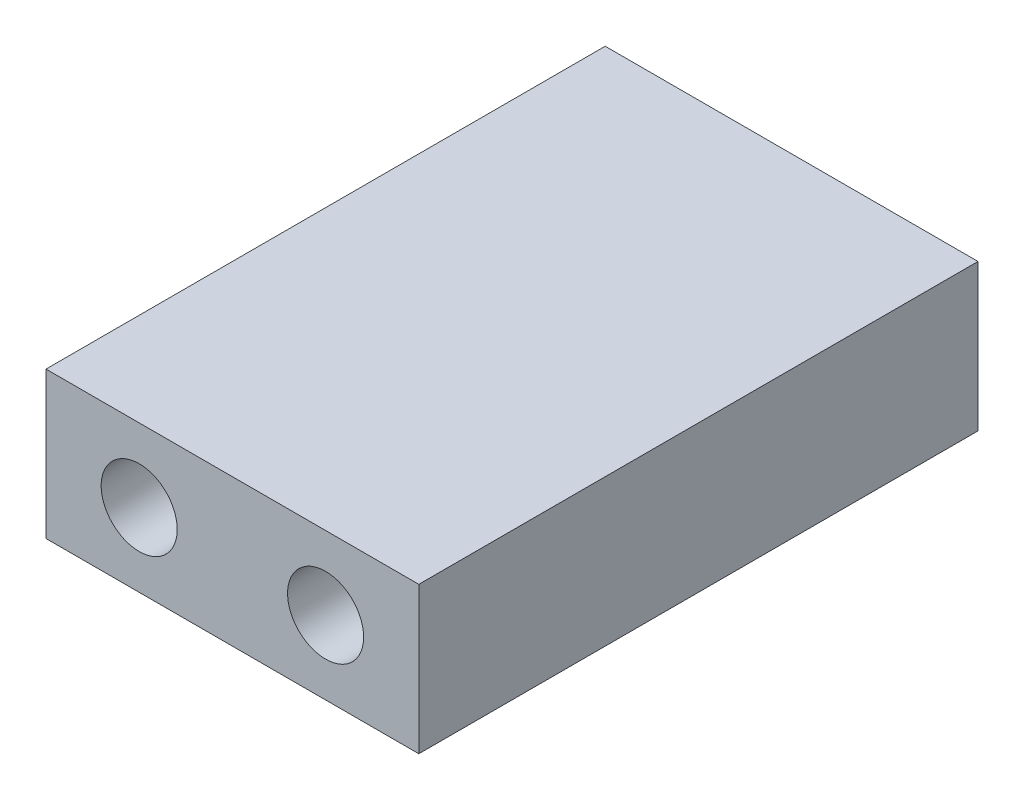
SolidWorks part; units mm, degrees
ref_plane "Front Plane" through (0, 0, 0) normal (0, 0, 1) x (1, 0, 0)
ref_plane "Top Plane" through (0, 0, 0) normal (0, 1, 0) x (1, 0, 0)
ref_plane "Right Plane" through (0, 0, 0) normal (1, 0, 0) x (0, 0, -1)
sketch "Sketch2" plane through (0, 0, 0) normal (0, 0, 1) x (1, 0, 0)
  line L1 (0, 0) -> (25.4, 0)
  line L2 (0, 0) -> (0, 10)
  line L3 (0, 10) -> (25.4, 10)
  line L4 (25.4, 0) -> (25.4, 10)
  point P5 (0, 0)
extrude "Boss-Extrude1" add sketch "Sketch2" along normal blind 38.1
sketch "Sketch3" plane through (0, 0, 38.1) normal (0, 0, 1) x (1, 0, 0)
  line L2 (25.4, 0) -> (25.4, 10) construction
  line L3 (0, -5.5) -> (0, 5.5) construction
  point P1 (19.05, 5)
  point P4 (6.35, 5)
  point P5 (0, 0)
  dimension "D1" = 6.35
  dimension "D2" = 6.35
hole_wizard "#6 (0.204) Diameter Hole1" positions "Sketch3" profile "Sketch4" hole size "#6" standard "ANSI Inch" end condition through all
sketch "Sketch4" plane through (19.05, 5, 38.1) normal (1, 0, 0) x (0, -1, 0)
  line L0 (0, 0) -> (0, 38.1)
  line L1 (0, 38.1) -> (2.5908, 38.1)
  line L2 (2.5908, 38.1) -> (2.5908, 0)
  line L5 (2.5908, 0) -> (0, 0)
  line L11 (0, -6.35) -> (0, 107.95) construction
  dimension "Thru Hole Dia." = 5.1816
  dimension "Thru Hole Depth" = 38.1
